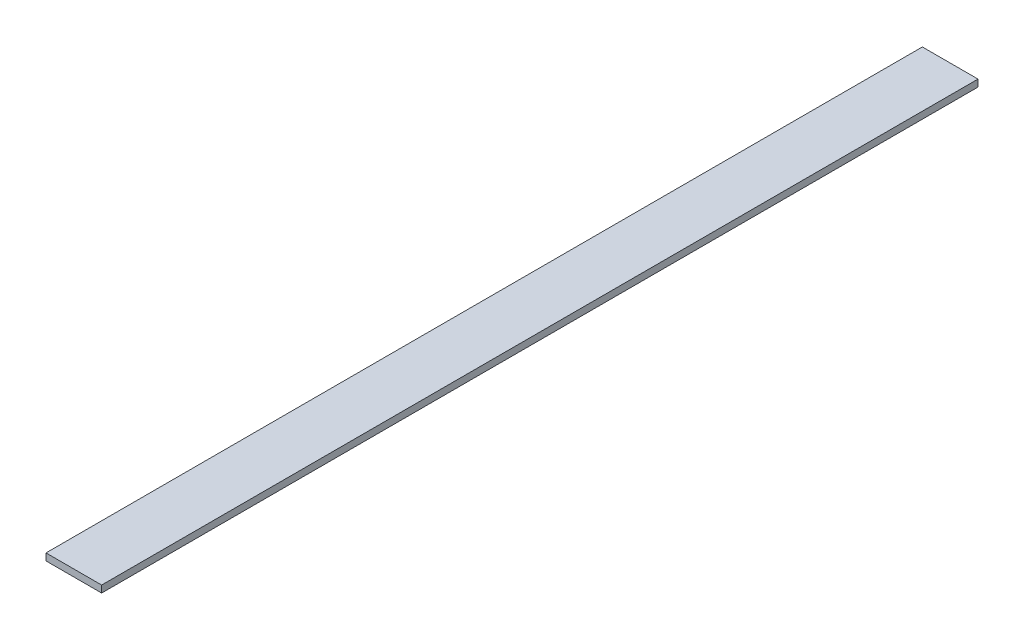
SolidWorks part; units mm, degrees
ref_plane "Front Plane" through (0, 0, 0) normal (0, 0, 1) x (1, 0, 0)
ref_plane "Top Plane" through (0, 0, 0) normal (0, 1, 0) x (1, 0, 0)
ref_plane "Right Plane" through (0, 0, 0) normal (1, 0, 0) x (0, 0, -1)
sketch "Sketch2" plane through (0, 0, 0) normal (0, 0, 1) x (1, 0, 0)
  line L1 (-7.1561, 3.2737) -> (43.6439, 3.2737)
  line L2 (-7.1561, 3.2737) -> (-7.1561, -3.0763)
  line L3 (-7.1561, -3.0763) -> (43.6439, -3.0763)
  line L4 (43.6439, 3.2737) -> (43.6439, -3.0763)
  dimension "D1" = 6.35
  dimension "D2" = 50.8
extrude "Boss-Extrude1" add sketch "Sketch2" against normal blind 800
